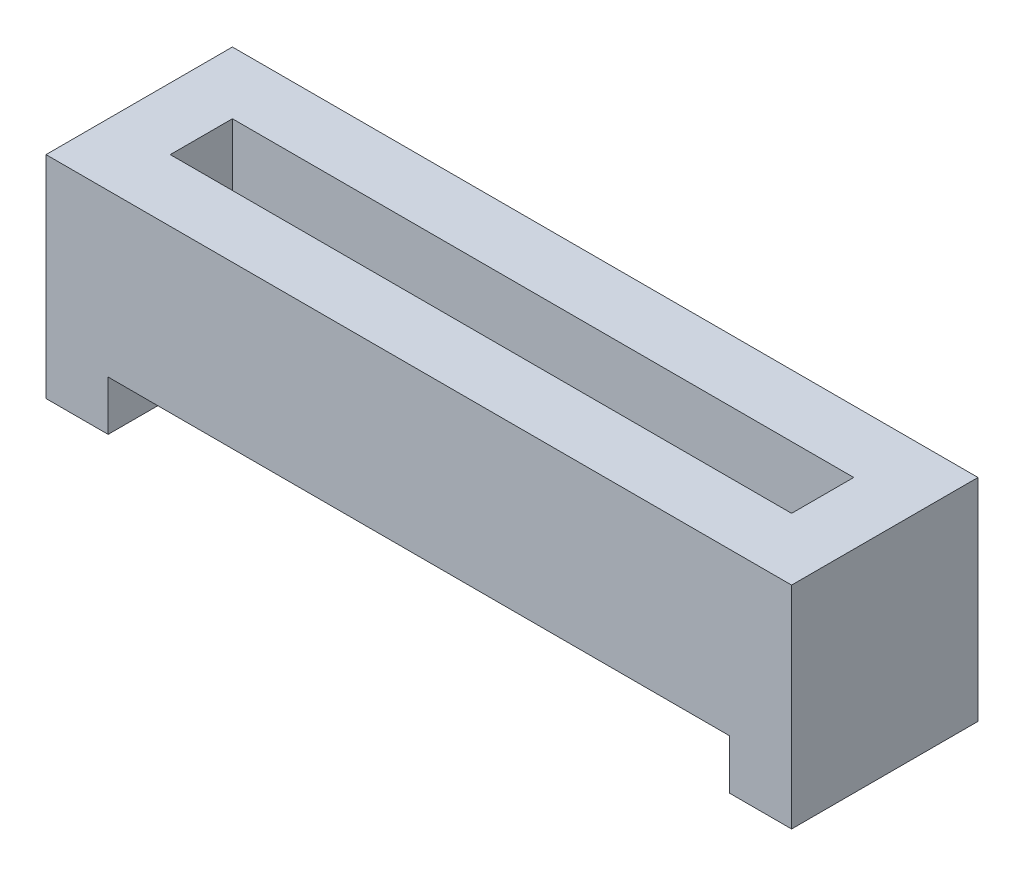
SolidWorks part; units mm, degrees
ref_plane "Front Plane" through (0, 0, 0) normal (0, 0, 1) x (1, 0, 0)
ref_plane "Top Plane" through (0, 0, 0) normal (0, 1, 0) x (1, 0, 0)
ref_plane "Right Plane" through (0, 0, 0) normal (1, 0, 0) x (0, 0, -1)
sketch "Sketch1" plane through (0, 0, 0) normal (0, 1, 0) x (1, 0, 0)
  line L1 (-30, -7.5) -> (30, -7.5)
  line L2 (-30, -7.5) -> (-30, 7.5)
  line L3 (-30, 7.5) -> (30, 7.5)
  line L4 (30, -7.5) -> (30, 7.5)
  line L5 (-30, -7.5) -> (30, 7.5) construction
  line L6 (-30, 7.5) -> (30, -7.5) construction
  point P0 (0, 0)
  dimension "D1" = 60
  dimension "D2" = 15
extrude "Boss-Extrude1" add sketch "Sketch1" along normal blind 13
sketch "Sketch2" plane through (0, 13, 0) normal (0, 1, 0) x (1, 0, 0)
  line L2 (-25, -2.5) -> (-25, 2.5)
  line L3 (-25, 2.5) -> (25, 2.5)
  line L4 (25, -2.5) -> (25, 2.5)
  line L5 (-25, -2.5) -> (25, 2.5) construction
  line L6 (-25, 2.5) -> (25, -2.5) construction
  line L13 (-25, -2.5) -> (25, -2.5)
  point P0 (0, 0)
  point P6 (-24.5943, -2.4594)
  point P8 (0, 0)
  point P9 (24.9007, 4.0729)
  point P10 (0, 0)
  dimension "D1" = 50
  dimension "D2" = 5
  dimension "D3" = 5
sketch "Sketch4" plane through (0, 0, 0) normal (0, -1, 0) x (-1, 0, 0)
  line L0 (-30, 7.5) -> (30, 7.5) construction
  line L1 (30, -7.5) -> (25, -7.5)
  line L2 (30, -7.5) -> (30, 7.5)
  line L3 (30, 7.5) -> (25, 7.5)
  line L4 (25, -7.5) -> (25, 7.5)
  dimension "D1" = 5
extrude "Boss-Extrude2" add sketch "Sketch4" along normal blind 4
mirror "Mirror1" about plane through (0, 0, 0) normal (1, 0, 0) of "Boss-Extrude2"
extrude "Cut-Extrude1" cut sketch "Sketch2" against normal blind 10
